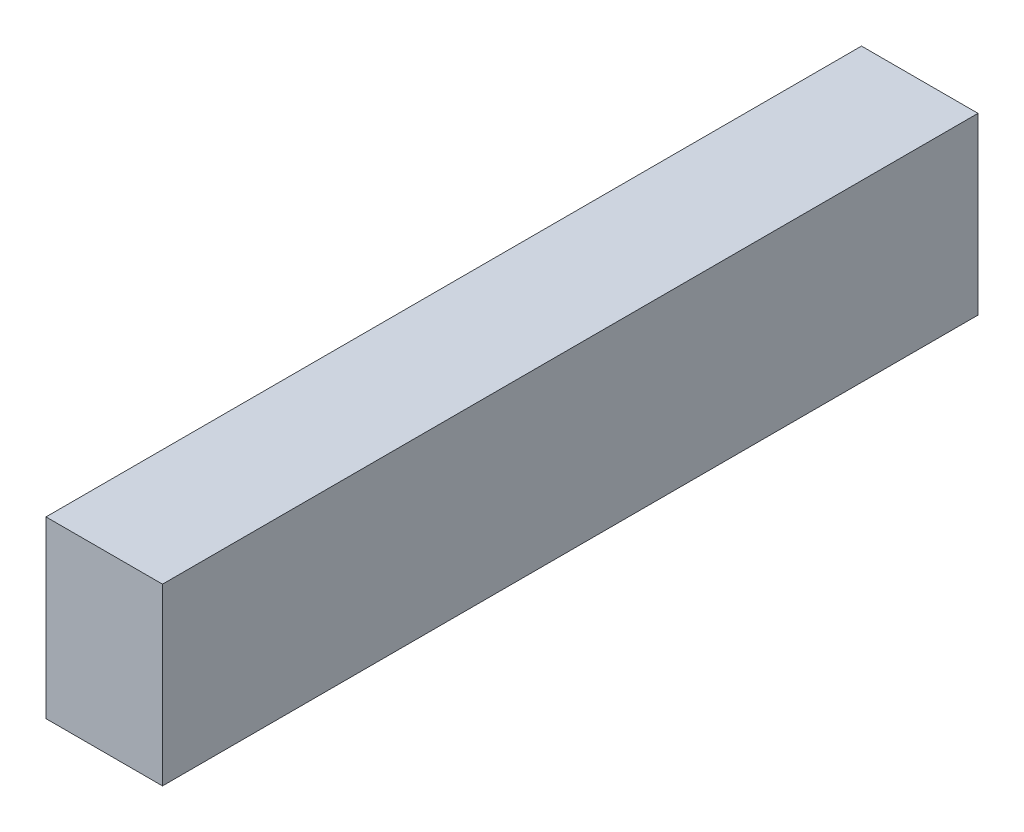
SolidWorks part; units mm, degrees
ref_plane "Front Plane" through (0, 0, 0) normal (0, 0, 1) x (1, 0, 0)
ref_plane "Top Plane" through (0, 0, 0) normal (0, 1, 0) x (1, 0, 0)
ref_plane "Right Plane" through (0, 0, 0) normal (1, 0, 0) x (0, 0, -1)
other "Configuration Table"
sketch "Sketch1" plane through (0, 0, 0) normal (0, 0, 1) x (1, 0, 0)
  line L1 (70, 1254) -> (90, 1254)
  line L2 (70, 1254) -> (70, 1284)
  line L3 (70, 1284) -> (90, 1284)
  line L4 (90, 1254) -> (90, 1284)
extrude "PRESS_uc_pence_parmak_1_1" add sketch "Sketch1" against normal blind 140 from offset 160 separate body
